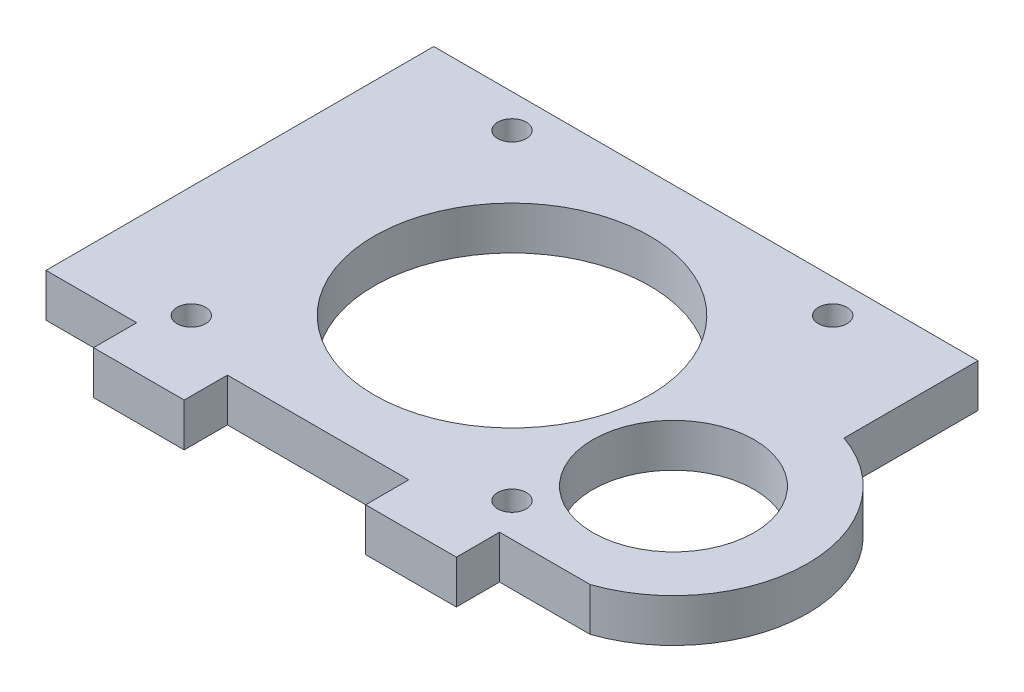
SolidWorks part; units mm, degrees
ref_plane "Alzado" through (0, 0, 0) normal (0, 0, 1) x (1, 0, 0)
ref_plane "Planta" through (0, 0, 0) normal (0, 1, 0) x (1, 0, 0)
ref_plane "Vista lateral" through (0, 0, 0) normal (1, 0, 0) x (0, 0, -1)
sketch "Sketch1" plane through (0, 0, 0) normal (0, 1, 0) x (1, 0, 0)
  line L1 (-40, 31.675) -> (40, 31.675)
  line L2 (-40, 31.675) -> (-40, -31.675)
  line L3 (-40, -31.675) -> (40, -31.675)
  line L4 (40, 31.675) -> (40, -31.675)
  line L5 (-40, 31.675) -> (40, -31.675) construction
  line L6 (-40, -31.675) -> (40, 31.675) construction
  point P0 (0, 0)
  dimension "D1" = 63.35
  dimension "D2" = 80
extrude "Boss-Extrude1" add sketch "Sketch1" along normal blind 6.35
sketch "Sketch2" plane through (0, 6.35, 0) normal (0, 1, 0) x (1, 0, 0)
  line L0 (-40, -31.675) -> (40, -31.675) construction
  line L1 (-40, -31.675) -> (-26.6667, -31.675)
  line L2 (-40, -31.675) -> (-40, -25.325)
  line L3 (-40, -25.325) -> (-26.6667, -25.325)
  line L4 (-26.6667, -31.675) -> (-26.6667, -25.325)
  line L5 (0, -31.675) -> (0, 0) construction
  line L7 (40, -25.325) -> (26.6667, -25.325)
  line L8 (26.6667, -31.675) -> (26.6667, -25.325)
  line L9 (40, -31.675) -> (26.6667, -31.675)
  line L10 (40, -31.675) -> (40, -25.325)
  line L11 (-40, 31.675) -> (-40, -31.675) construction
  line L17 (-13.3333, -31.675) -> (13.3333, -31.675)
  line L18 (-13.3333, -31.675) -> (-13.3333, -25.325)
  line L19 (-13.3333, -25.325) -> (13.3333, -25.325)
  line L20 (13.3333, -31.675) -> (13.3333, -25.325)
  dimension "D1" = 6.35
  dimension "D2" = 13.3333
  dimension "D3" = 26.6667
  dimension "D4" = 13.3333
extrude "Cut-Extrude2" cut sketch "Sketch2" against normal through all
sketch "Sketch3" plane through (0, 6.35, 0) normal (0, 1, 0) x (1, 0, 0)
  line L1 (40, 31.675) -> (-40, 31.675) construction
  line L2 (-28.5, -25.325) -> (28.5, -25.325) construction
  line L3 (-28.5, -25.325) -> (-28.5, 31.675) construction
  line L4 (-28.5, 31.675) -> (28.5, 31.675) construction
  line L5 (28.5, -25.325) -> (28.5, 31.675) construction
  line L6 (-28.5, -25.325) -> (28.5, 31.675) construction
  line L7 (-28.5, 31.675) -> (28.5, -25.325) construction
  circle A0 centre (0, 3.175) radius 20.25
  dimension "D1" = 57
  dimension "D2" = 40.5
  dimension "D3" = 57
extrude "Cut-Extrude3" cut sketch "Sketch3" against normal blind 2.55
sketch "Sketch4" plane through (0, 6.35, 0) normal (0, 1, 0) x (1, 0, 0)
  circle A0 centre (0, 3.175) radius 20.25 construction
  circle A1 centre (0, 3.175) radius 20.25
extrude "Cut-Extrude4" cut sketch "Sketch4" against normal through all
sketch "Sketch5" plane through (0, 6.35, 0) normal (0, 1, 0) x (1, 0, 0)
  line L1 (-23.57, -20.395) -> (23.57, -20.395) construction
  line L2 (-23.57, -20.395) -> (-23.57, 26.745) construction
  line L3 (-23.57, 26.745) -> (23.57, 26.745) construction
  line L4 (23.57, -20.395) -> (23.57, 26.745) construction
  line L5 (-23.57, -20.395) -> (23.57, 26.745) construction
  line L6 (-23.57, 26.745) -> (23.57, -20.395) construction
  circle A2 centre (0, 3.175) radius 8.5 construction
  circle A3 centre (23.57, 26.745) radius 2.1
  circle A4 centre (-23.57, 26.745) radius 2.1
  circle A5 centre (-23.57, -20.395) radius 2.1
  circle A6 centre (23.57, -20.395) radius 2.1
  circle A7 centre (0, 3.175) radius 20.25 construction
  point P18 (0, 3.175)
  dimension "D1" = 47.14
  dimension "D2" = 4.2
  dimension "D4" = 17
  dimension "D3" = 4
extrude "Cut-Extrude5" cut sketch "Sketch5" against normal through all
sketch "Sketch6" plane through (0, 6.35, 0) normal (0, 1, 0) x (1, 0, 0)
  line L0 (-28.5, -25.325) -> (28.5, 31.675) construction
  circle A0 centre (0, 3.175) radius 18.0674
  dimension "D1" = 36.1349
extrude "Cut-Extrude6" [suppressed] cut sketch "Sketch6" against normal up to next
sketch "Sketch7" [suppressed] plane through (0, 6.35, 0) normal (0, 1, 0) x (1, 0, 0)
  line L0 (-21.5142, 15.9084) -> (-40, -15.325)
  line L1 (-40, 31.675) -> (-40, -25.325) construction
  line L2 (21.5142, 15.9084) -> (40, -15.325)
  line L3 (40, -25.325) -> (40, 31.675) construction
  line L16 (-40, -25.325) -> (-27.1667, -25.325)
  line L17 (-26.6667, -25.825) -> (-26.6667, -31.675)
  line L18 (-26.6667, -31.675) -> (-13.3333, -31.675)
  line L19 (-13.3333, -31.675) -> (-13.3333, -25.825)
  line L20 (-12.8333, -25.325) -> (12.8333, -25.325)
  line L21 (13.3333, -25.825) -> (13.3333, -31.675)
  line L22 (13.3333, -31.675) -> (26.6667, -31.675)
  line L23 (26.6667, -31.675) -> (26.6667, -25.825)
  line L24 (27.1667, -25.325) -> (40, -25.325)
  line L25 (40, -25.325) -> (40, 31.675)
  line L26 (40, 31.675) -> (-40, 31.675)
  line L27 (-40, 31.675) -> (-40, -25.325)
  line L28 (-40, -25.325) -> (-27.1667, -25.325)
  line L29 (-26.6667, -25.825) -> (-26.6667, -31.675)
  line L30 (-26.6667, -31.675) -> (-13.3333, -31.675)
  line L31 (-13.3333, -31.675) -> (-13.3333, -25.825)
  line L32 (-12.8333, -25.325) -> (12.8333, -25.325)
  line L33 (13.3333, -25.825) -> (13.3333, -31.675)
  line L34 (13.3333, -31.675) -> (26.6667, -31.675)
  line L35 (26.6667, -31.675) -> (26.6667, -25.825)
  line L36 (27.1667, -25.325) -> (40, -25.325)
  line L37 (40, -25.325) -> (40, -15.325)
  line L39 (-40, -15.325) -> (-40, -25.325)
  arc A0 (21.5142, 15.9084) -> (-21.5142, 15.9084) centre (0, 3.175) ccw
  arc A5 (-26.6667, -25.825) -> (-27.1667, -25.325) centre (-26.6667, -25.325) ccw
  arc A6 (-12.8333, -25.325) -> (-13.3333, -25.825) centre (-13.3333, -25.325) ccw
  arc A7 (13.3333, -25.825) -> (12.8333, -25.325) centre (13.3333, -25.325) ccw
  arc A8 (27.1667, -25.325) -> (26.6667, -25.825) centre (26.6667, -25.325) ccw
  arc A9 (-26.6667, -25.825) -> (-27.1667, -25.325) centre (-26.6667, -25.325) ccw
  arc A10 (-12.8333, -25.325) -> (-13.3333, -25.825) centre (-13.3333, -25.325) ccw
  arc A11 (13.3333, -25.825) -> (12.8333, -25.325) centre (13.3333, -25.325) ccw
  arc A12 (27.1667, -25.325) -> (26.6667, -25.825) centre (26.6667, -25.325) ccw
  dimension "D1" = 0
  dimension "D3" = 50
  dimension "D2" = 10
extrude "Cut-Extrude7" [suppressed] cut sketch "Sketch7" against normal up to next flip side to cut
sketch "Sketch8" [suppressed] plane through (0, 6.35, 0) normal (0, 1, 0) x (1, 0, 0)
  circle A0 centre (0, 3.175) radius 18.5 construction
  dimension "D1" = 37
hole_wizard "M5 Tapped Hole1" [suppressed] positions "Sketch9" profile "Sketch10" tap size "M5" standard "ISO"
sketch "Sketch9" plane through (0, 6.35, 0) normal (0, 1, 0) x (1, 0, 0)
  circle A0 centre (0, 3.175) radius 18.5 construction
  point P0 (0, 21.675)
  point P4 (18.5, 3.175)
  point P6 (0, -15.325)
  point P8 (-18.5, 3.175)
sketch "Sketch10" plane through (0, 6.35, -21.675) normal (1, 0, 0) x (0, 0, 1)
  line L0 (0, 0) -> (0, 6.35)
  line L1 (0, 6.35) -> (2.1, 6.35)
  line L2 (2.1, 6.35) -> (2.1, 0)
  line L5 (2.1, 0) -> (0, 0)
  line L11 (0, -6.35) -> (0, 107.95) construction
  dimension "Thru Tap Drill Dia." = 4.2
  dimension "Thru Tap Drill Depth" = 6.35
sketch "Sketch11" plane through (0, 0, 0) normal (0, -1, 0) x (1, 0, 0)
  line L0 (13.3333, 31.675) -> (26.6667, 31.675) construction
  circle A0 centre (33.5854, 6.675) radius 11.85
  circle A1 centre (0, -3.175) radius 20.25 construction
  circle A2 centre (0, -3.175) radius 20.25 construction
  dimension "D1" = 23.7
  dimension "D2" = 35
  dimension "D3" = 25
sketch "Sketch12" plane through (0, 0, 0) normal (0, -1, 0) x (1, 0, 0)
  line L0 (40, 25.325) -> (40, -11.975)
  line L1 (40, 25.325) -> (40, -31.675) construction
  arc A0 (40, -11.975) -> (40, 25.325) centre (33.5854, 6.675) ccw
extrude "Boss-Extrude2" add sketch "Sketch12" against normal up to surface (6.35 mm away) up to face at (23.57, 6.35, 22.495)
sketch "Sketch13" plane through (0, 0, 0) normal (0, -1, 0) x (1, 0, 0)
  circle A0 centre (33.5854, 6.675) radius 11.85
  circle A1 centre (33.5854, 6.675) radius 11.85 construction
extrude "Cut-Extrude8" cut sketch "Sketch13" against normal blind 10
sketch "Sketch14" [suppressed] plane through (0, 0, 0) normal (0, -1, 0) x (1, 0, 0)
  line L0 (-26.6667, 31.675) -> (-13.3333, 31.675) construction
  circle A0 centre (0, -3.175) radius 9.5 construction
  circle A1 centre (0, -3.175) radius 9.5
  circle A2 centre (-33.5854, 6.675) radius 11.85
  dimension "D1" = 23.7
  dimension "D2" = 35
  dimension "D3" = 25
sketch "Sketch15" [suppressed] plane through (0, 0, 0) normal (0, -1, 0) x (1, 0, 0)
  line L0 (-40, 25.325) -> (-40, 15.325)
  line L1 (-40, 15.325) -> (-24.5152, -10.8379)
  line L2 (-40, 15.325) -> (-21.5142, -15.9084) construction
  arc A0 (-40, 25.325) -> (-24.5152, -10.8379) centre (-33.5854, 6.675) ccw
extrude "Boss-Extrude3" [suppressed] add sketch "Sketch15" against normal up to surface (6.35 mm away)
sketch "Sketch16" [suppressed] plane through (0, 0, 0) normal (0, -1, 0) x (1, 0, 0)
  circle A0 centre (-33.5854, 6.675) radius 11.85
  circle A1 centre (-33.5854, 6.675) radius 11.85 construction
extrude "Cut-Extrude9" [suppressed] cut sketch "Sketch16" against normal blind 10
